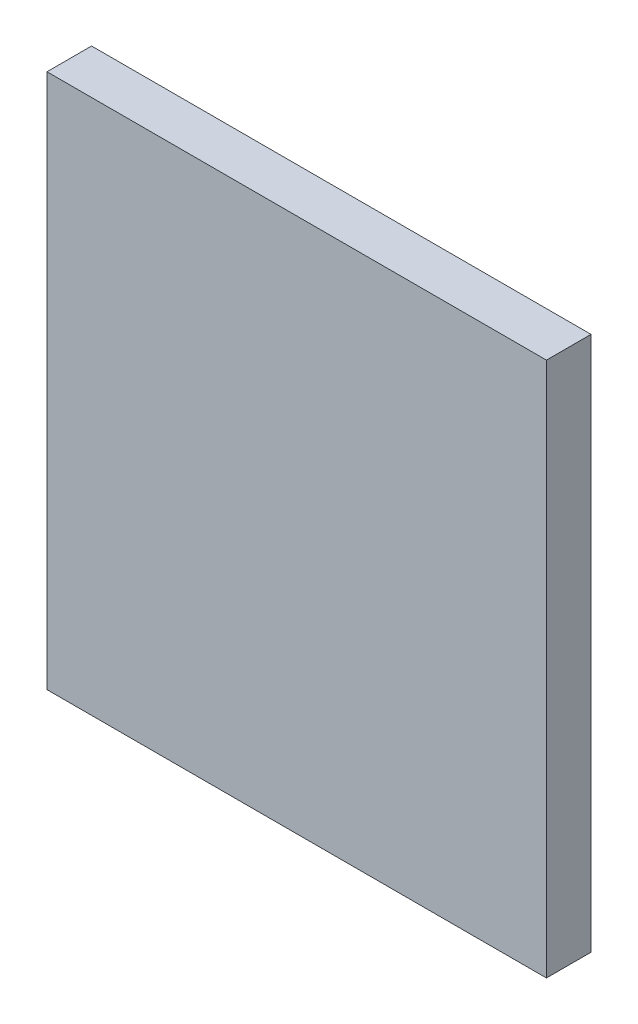
SolidWorks part; units mm, degrees
ref_plane "前视基准面" through (0, 0, 0) normal (0, 0, 1) x (1, 0, 0)
ref_plane "上视基准面" through (0, 0, 0) normal (0, 1, 0) x (1, 0, 0)
ref_plane "右视基准面" through (0, 0, 0) normal (1, 0, 0) x (0, 0, -1)
other "Configuration Table"
sketch "草图1" plane through (0, 0, 0) normal (0, 0, 1) x (1, 0, 0)
  line L0 (0, 0) -> (56, 0)
  line L1 (56, 0) -> (56, 60)
  line L2 (56, 60) -> (0, 60)
  line L3 (0, 60) -> (0, 0)
  dimension "width" = 56
  dimension "height" = 60
extrude "Fixed_Base" add sketch "草图1" along normal blind 5
